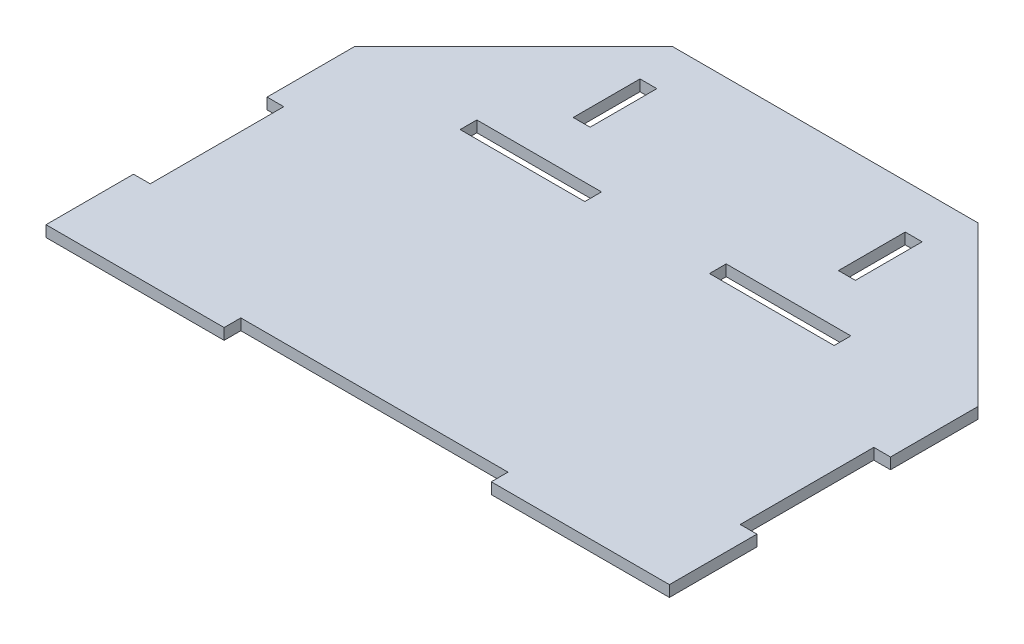
SolidWorks part; units mm, degrees
ref_plane "Front Plane" through (0, 0, 0) normal (0, 0, 1) x (1, 0, 0)
ref_plane "Top Plane" through (0, 0, 0) normal (0, 1, 0) x (1, 0, 0)
ref_plane "Right Plane" through (0, 0, 0) normal (1, 0, 0) x (0, 0, -1)
sketch "Sketch1" plane through (0, 0, 0) normal (0, 1, 0) x (1, 0, 0)
  line L0 (-177.8, 42.672) -> (-87.122, 133.35)
  line L1 (-177.8, -133.35) -> (-76.2, -133.35)
  line L2 (-177.8, -133.35) -> (-177.8, -83.439)
  line L3 (-87.122, 133.35) -> (87.122, 133.35)
  line L4 (177.8, -133.35) -> (177.8, -83.439)
  line L5 (-177.8, -133.35) -> (125.984, 94.488) construction
  line L6 (-125.984, 94.488) -> (177.8, -133.35) construction
  line L7 (0, 133.35) -> (0, -133.35) construction
  line L8 (-177.8, -83.439) -> (-168.275, -83.439)
  line L10 (-177.8, -7.239) -> (-168.275, -7.239)
  line L11 (-168.275, -83.439) -> (-168.275, -7.239)
  line L12 (-38.1, 133.35) -> (38.1, 133.35)
  line L14 (-76.2, -133.35) -> (-76.2, -123.825)
  line L15 (-76.2, -123.825) -> (76.2, -123.825)
  line L16 (76.2, -133.35) -> (76.2, -123.825)
  line L17 (177.8, 42.672) -> (87.122, 133.35)
  line L18 (177.8, -7.239) -> (168.275, -7.239)
  line L19 (168.275, -83.439) -> (168.275, -7.239)
  line L20 (177.8, -83.439) -> (168.275, -83.439)
  line L22 (177.8, -7.239) -> (177.8, 42.672)
  line L23 (76.2, -133.35) -> (177.8, -133.35)
  line L24 (-177.8, -7.239) -> (-177.8, 42.672)
  point P0 (0, 0)
  point P12 (-168.275, -45.339)
  point P14 (0, -123.825)
  dimension "D1" = 355.6
  dimension "D2" = 266.7
  dimension "D5" = 76.2
  dimension "D6" = 88.011
  dimension "D3" = 176.022
  dimension "D4" = 135
  dimension "D7" = 9.525
  dimension "D8" = 152.4
  dimension "D9" = 177.8
  dimension "D10" = 9.525
extrude "Boss-Extrude1" add sketch "Sketch1" along normal blind 6.35 contours L24 L10 L11 L8 L2 L1 L14 L15 L16 L23 L4 L20 L19 L18 L22 L17 L3 L0
sketch "Sketch2" plane through (0, 6.35, 0) normal (0, 1, 0) x (1, 0, 0)
  line L1 (177.8, -7.239) -> (177.8, 42.672) construction
  line L2 (106.68, 41.275) -> (35.56, 41.275)
  line L3 (106.68, 41.275) -> (106.68, 31.75)
  line L4 (106.68, 31.75) -> (35.56, 31.75)
  line L5 (35.56, 41.275) -> (35.56, 31.75)
  line L6 (0, -3.4925) -> (0, 3.4925) construction
  line L7 (-35.56, 41.275) -> (-35.56, 31.75)
  line L8 (-106.68, 31.75) -> (-35.56, 31.75)
  line L9 (-106.68, 41.275) -> (-106.68, 31.75)
  line L10 (-106.68, 41.275) -> (-35.56, 41.275)
  line L12 (76.2, -133.35) -> (177.8, -133.35) construction
  dimension "D1" = 71.12
  dimension "D2" = 71.12
  dimension "D3" = 9.525
  dimension "D4" = 165.1
extrude "Cut-Extrude1" cut sketch "Sketch2" against normal through all
sketch "Sketch3" plane through (0, 6.35, 0) normal (0, 1, 0) x (1, 0, 0)
  line L5 (80.5288, 69.977) -> (70.8768, 69.977)
  line L6 (80.5288, 69.977) -> (80.5288, 108.077)
  line L7 (80.5288, 108.077) -> (70.8768, 108.077)
  line L8 (70.8768, 69.977) -> (70.8768, 108.077)
  line L13 (-80.4077, 69.977) -> (-70.7863, 69.977)
  line L14 (-80.4077, 69.977) -> (-80.4077, 108.077)
  line L15 (-80.4077, 108.077) -> (-70.7863, 108.077)
  line L16 (-70.7863, 69.977) -> (-70.7863, 108.077)
extrude "Cut-Extrude2" cut sketch "Sketch3" against normal blind 6.35
equation "\"D6@Sketch1\"=\"D3@Sketch1\"/2"
equation "\"D9@Sketch1\"=\"D1@Sketch1\"/2"
